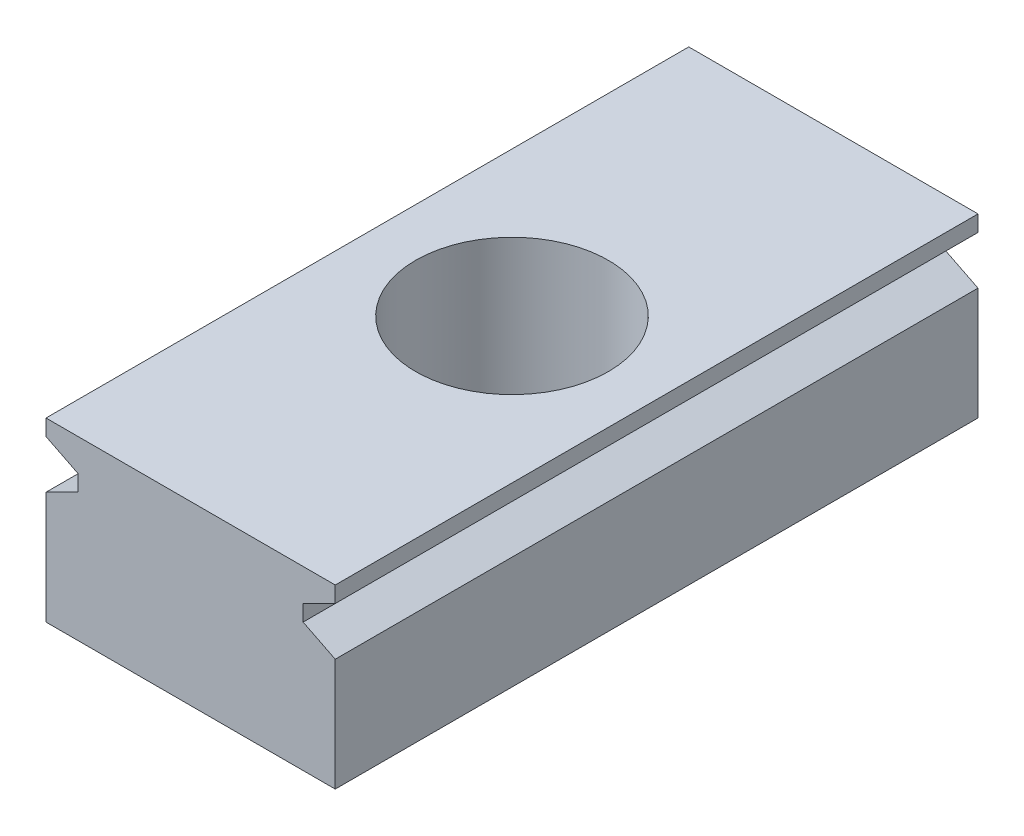
SolidWorks part; units mm, degrees
ref_plane "Plan de face" through (0, 0, 0) normal (0, 0, 1) x (1, 0, 0)
ref_plane "Plan de dessus" through (0, 0, 0) normal (0, 1, 0) x (1, 0, 0)
ref_plane "Plan de droite" through (0, 0, 0) normal (1, 0, 0) x (0, 0, -1)
sketch "Esquisse1" plane through (0, 0, 0) normal (0, 0, 1) x (1, 0, 0)
  line L0 (-4.5, 0) -> (4.5, 0)
  line L1 (4.5, 0) -> (4.5, 3.5)
  line L2 (4.5, 3.5) -> (3.5, 4)
  line L3 (3.5, 4) -> (3.5, 4.5)
  line L4 (3.5, 4.5) -> (4.5, 5)
  line L5 (4.5, 5) -> (4.5, 5.5)
  line L6 (4.5, 5.5) -> (-4.5, 5.5)
  line L7 (-4.5, 5.5) -> (-4.5, 5)
  line L8 (-4.5, 5) -> (-3.5, 4.5)
  line L9 (-3.5, 4.5) -> (-3.5, 4)
  line L10 (-3.5, 4) -> (-4.5, 3.5)
  line L11 (-4.5, 3.5) -> (-4.5, 0)
  line L12 (0, 0) -> (0, 12.6473) construction
  point P15 (0, 0)
  point P16 (0, 0)
  point P17 (1.8818, 3.034)
  point P18 (0, 0)
  point P19 (0, 0)
  point P20 (-4.5271, 4.8067)
  point P21 (0, 0)
  dimension "D1" = 9
  dimension "D2" = 5.5
  dimension "D3" = 1
  dimension "D4" = 9
  dimension "D5" = 1.5
  dimension "D6" = 0.5
  dimension "D7" = 0.5
  dimension "D8" = 7
extrude "Boss.-Extru.1" add sketch "Esquisse1" along normal blind 20
sketch "Esquisse2" plane through (0, 5.5, 0) normal (0, 1, 0) x (1, 0, 0)
  line L0 (0, -20) -> (0, 0) construction
  line L1 (4.5, -20) -> (-4.5, -20) construction
  line L2 (4.5, 0) -> (-4.5, 0) construction
  circle A0 centre (0, -10) radius 3
  dimension "D1" = 6
extrude "Enlèv. mat.-Extru.1" cut sketch "Esquisse2" against normal blind 4.5
sketch "Esquisse3" plane through (0, 1, 0) normal (0, 1, 0) x (1, 0, 0)
  circle A0 centre (0, -10) radius 1.75
  dimension "D1" = 3.5
extrude "Enlèv. mat.-Extru.2" cut sketch "Esquisse3" against normal through all
